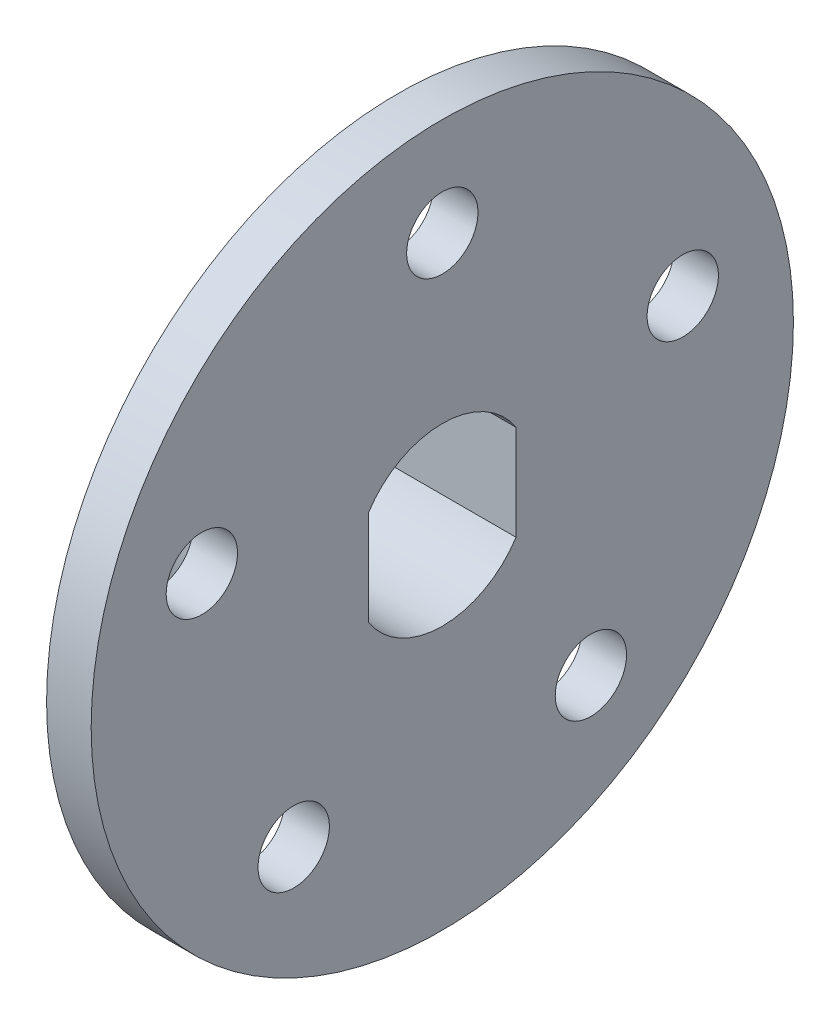
SolidWorks part; units mm, degrees
material "6061-T6 (SS)"
ref_plane "Front Plane" through (0, 0, 0) normal (0, 0, 1) x (1, 0, 0)
ref_plane "Top Plane" through (0, 0, 0) normal (0, 1, 0) x (1, 0, 0)
ref_plane "Right Plane" through (0, 0, 0) normal (1, 0, 0) x (0, 0, -1)
sketch "Sketch1" plane through (0, 0, 0) normal (1, 0, 0) x (0, 0, -1)
  line L0 (-5.25, 3.3912) -> (-5.25, -3.3912)
  line L1 (5.25, 3.3912) -> (5.25, -3.3912)
  circle A0 centre (0, 0) radius 11
  arc A1 (-5.25, -3.3912) -> (5.25, -3.3912) centre (0, 0) ccw
  arc A2 (5.25, 3.3912) -> (-5.25, 3.3912) centre (0, 0) ccw
  dimension "D1" = 12.5
  dimension "D2" = 22
  dimension "D3" = 10.5
extrude "Boss-Extrude1" add sketch "Sketch1" along normal blind 5.925
sketch "Sketch2" plane through (5.925, 0, 0) normal (1, 0, 0) x (0, 0, -1)
  line L0 (-5.25, 3.3912) -> (-5.25, -3.3912)
  line L1 (5.25, -3.3912) -> (5.25, 3.3912)
  line L2 (-5.25, 3.3912) -> (-5.25, -3.3912) construction
  circle A0 centre (0, 0) radius 25
  circle A1 centre (0, 0) radius 6.25 construction
  arc A2 (-5.25, -3.3912) -> (5.25, -3.3912) centre (0, 0) ccw
  arc A3 (5.25, 3.3912) -> (-5.25, 3.3912) centre (0, 0) ccw
  dimension "D1" = 50
extrude "Boss-Extrude2" add sketch "Sketch2" along normal blind 3.175
sketch "Sketch3" plane through (5.925, 0, 0) normal (-1, 0, 0) x (0, 0, 1)
  line L0 (0, 25) -> (0, 18) construction
  circle A0 centre (0, 0) radius 25 construction
  circle A1 centre (0, 18) radius 2.54
  circle A2 centre (17.119, 5.5623) radius 2.54
  circle A3 centre (10.5801, -14.5623) radius 2.54
  circle A4 centre (-10.5801, -14.5623) radius 2.54
  circle A5 centre (-17.119, 5.5623) radius 2.54
  point P18 (0, 0)
  dimension "D1" = 5.08
  dimension "D2" = 7
  dimension "D3" = 5
extrude "Cut-Extrude1" cut sketch "Sketch3" against normal through all
